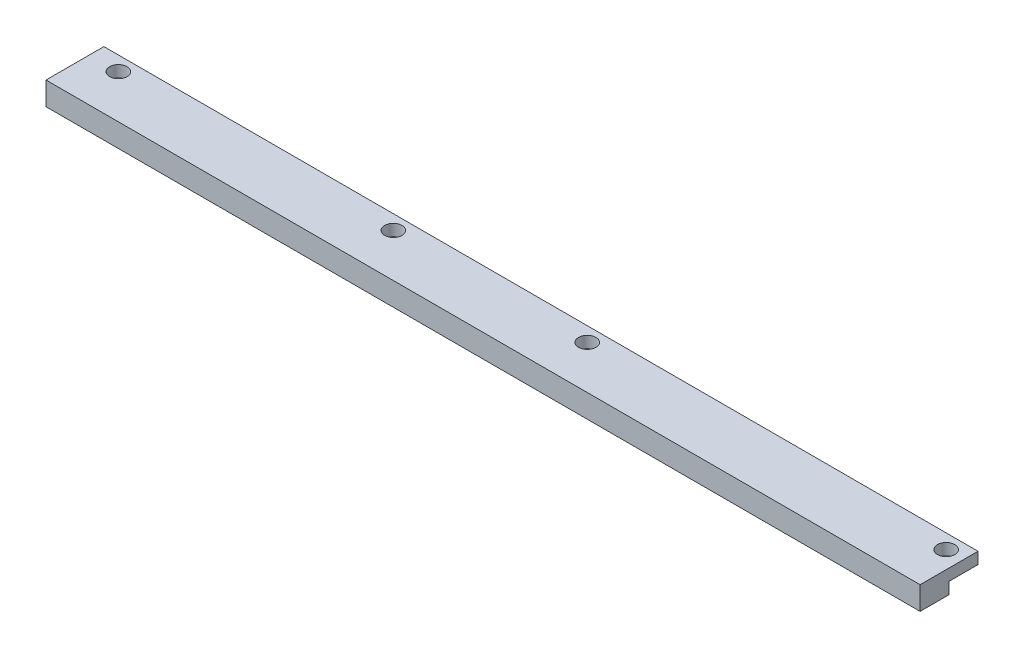
SolidWorks part; units mm, degrees
ref_plane "前视基准面" through (0, 0, 0) normal (0, 0, 1) x (1, 0, 0)
ref_plane "上视基准面" through (0, 0, 0) normal (0, 1, 0) x (1, 0, 0)
ref_plane "右视基准面" through (0, 0, 0) normal (1, 0, 0) x (0, 0, -1)
other "Configuration Table"
sketch "草图1" plane through (0, 0, 0) normal (0, 1, 0) x (1, 0, 0)
  line L1 (0, -5) -> (151, -5)
  line L2 (0, -5) -> (0, 0)
  line L3 (0, 0) -> (151, 0)
  line L4 (151, -5) -> (151, 0)
  circle A2 centre (5, -2.5) radius 1.5
  circle A3 centre (52.5, -2.5) radius 1.5
  circle A4 centre (86, -2.5) radius 1.5
  circle A5 centre (148, -2.5) radius 1.5
  point P8 (86, -2.5)
  point P9 (0, -2.5)
  point P14 (52.5, -2.5)
  point P15 (142.8339, -2.5)
  point P16 (148, -2.5)
  point P17 (86, -2.5)
  point P18 (52.5, -2.5)
  dimension "D1" = 3
  dimension "D2" = 5
  dimension "D3" = 5
  dimension "D4" = 3
extrude "凸台-拉伸1" add sketch "草图1" along normal blind 2 contours L3 L4 L1 L2 | A2 | A3 | A4 | A5
sketch "草图2" plane through (0, 0, 0) normal (0, 1, 0) x (1, 0, 0)
  line L0 (151, -5) -> (151, 0) construction
  line L1 (0, -5) -> (151, -5)
  line L2 (0, -5) -> (0, -10)
  line L3 (0, -10) -> (151, -10)
  line L4 (151, -5) -> (151, -10)
  dimension "D1" = 5
extrude "凸台-拉伸2" add sketch "草图2" against normal blind 4 from surface at 2 starting at face at (75.5, 2, 2.5)
